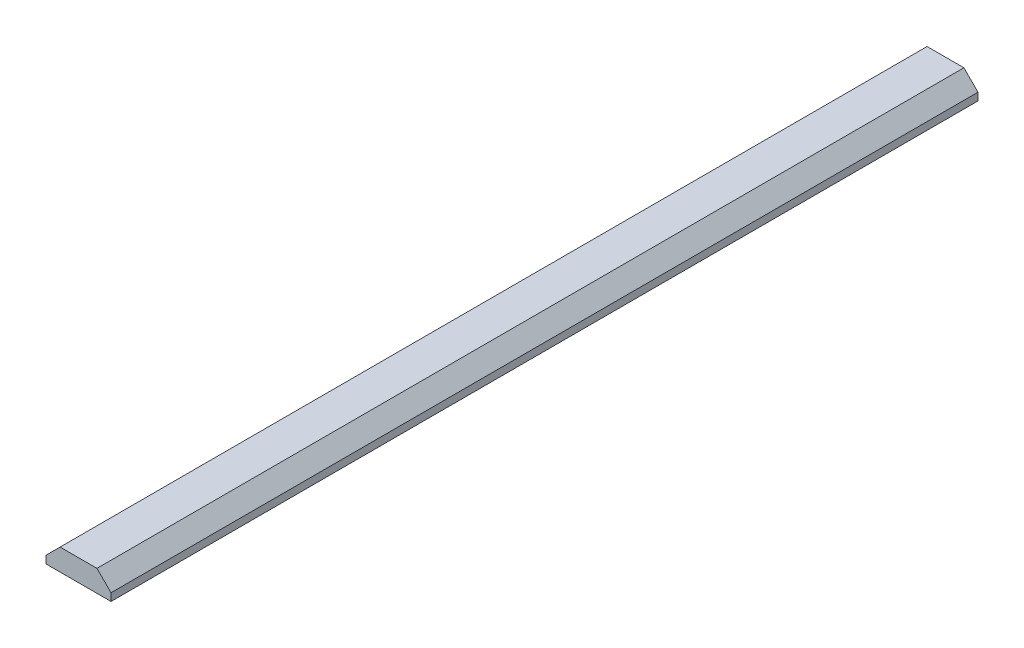
SolidWorks part; units mm, degrees
ref_plane "Ebene vorne" through (0, 0, 0) normal (0, 0, 1) x (1, 0, 0)
ref_plane "Ebene oben" through (0, 0, 0) normal (0, 1, 0) x (1, 0, 0)
ref_plane "Ebene rechts" through (0, 0, 0) normal (1, 0, 0) x (0, 0, -1)
sketch "Skizze1" plane through (0, 0, 0) normal (0, 0, 1) x (1, 0, 0)
  line L0 (0, 0) -> (0, 23680.6173) construction
  line L1 (3.4, 1.8089) -> (-3.4, 1.8089)
  line L2 (-3.4, 1.8089) -> (-6, -0.7911)
  line L3 (-6, -0.7911) -> (-6, -2.1911)
  line L4 (-6, -2.1911) -> (6, -2.1911)
  line L5 (6, -0.7911) -> (6, -2.1911)
  line L6 (3.4, 1.8089) -> (6, -0.7911)
  point P9 (0, -2.1911)
  point P11 (0, 1.8089)
  dimension "D1" = 3.4
  dimension "D2" = 6
  dimension "D3" = 4
  dimension "D4" = 135
extrude "Aufsatz-Linear austragen1" add sketch "Skizze1" along normal blind 160 contours L1 L2 L3 L4 L5 L6
